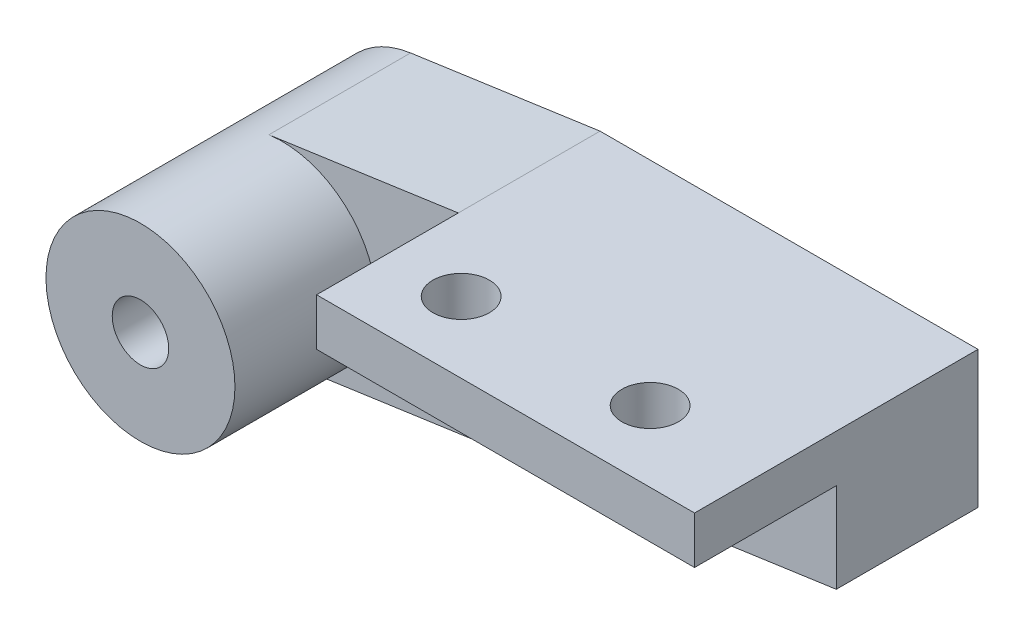
SolidWorks part; units mm, degrees
material "Custom Plastic"
ref_plane "Front Plane" through (0, 0, 0) normal (0, 0, 1) x (1, 0, 0)
ref_plane "Top Plane" through (0, 0, 0) normal (0, 1, 0) x (1, 0, 0)
ref_plane "Right Plane" through (0, 0, 0) normal (1, 0, 0) x (0, 0, -1)
sketch "Sketch1" plane through (0, 0, 0) normal (0, 0, 1) x (1, 0, 0)
  line L0 (0, 0) -> (11.8364, 0) construction
  line L1 (11.8364, 0) -> (11.8364, 8.1026) construction
  line L2 (11.8364, 8.1026) -> (-0.8967, 6.2864)
  line L3 (0.8967, -6.2864) -> (37.2364, -1.1029)
  line L4 (11.8364, 8.1026) -> (37.2364, 8.1026)
  line L5 (37.2364, 8.1026) -> (37.2364, -1.1029)
  arc A0 (-0.8967, 6.2864) -> (0.8967, -6.2864) centre (0, 0) ccw
  dimension "D3" = 12.7
  dimension "D1" = 11.8364
  dimension "D2" = 8.1026
  dimension "D4" = 25.4
extrude "Boss-Extrude1" add sketch "Sketch1" along normal blind 9.525
sketch "Sketch4" plane through (0, 0, 9.525) normal (0, 0, 1) x (1, 0, 0)
  line L0 (37.2364, -1.1029) -> (37.2364, 8.1026) construction
  line L1 (37.2364, 8.1026) -> (11.8364, 8.1026)
  line L2 (37.2364, 8.1026) -> (37.2364, 4.9276)
  line L3 (37.2364, 4.9276) -> (11.8364, 4.9276)
  line L4 (11.8364, 8.1026) -> (11.8364, 4.9276)
  line L5 (37.2364, 8.1026) -> (11.8364, 8.1026) construction
  circle A0 centre (0, 0) radius 6.35
  arc A1 (-0.8967, 6.2864) -> (0.8967, -6.2864) centre (0, 0) ccw construction
  dimension "D1" = 3.175
extrude "Boss-Extrude2" add sketch "Sketch4" along normal blind 9.525
hole_wizard "#6 Clearance Hole1" positions "3DSketch2" profile "Sketch3" hole size "#6" standard "ANSI Inch" end condition through all
sketch3d "3DSketch2"
  point P11 (0, 0, 0)
sketch "Sketch3" plane through (0, 0, 0) normal (1, 0, 0) x (0, 1, 0)
  line L0 (0, 0) -> (0, 19.05)
  line L1 (0, 19.05) -> (1.8986, 19.05)
  line L2 (1.8986, 19.05) -> (1.8986, 0)
  line L5 (1.8986, 0) -> (0, 0)
  line L11 (0, -6.35) -> (0, 107.95) construction
  dimension "Thru Hole Dia." = 3.7973
  dimension "Thru Hole Depth" = 19.05
hole_wizard "#6 Clearance Hole2" positions "3DSketch3" profile "Sketch5" hole size "#6" standard "ANSI Inch" end condition through all
sketch3d "3DSketch3"
  line L0 (16.7894, 4.9276, 14.2875) -> (29.4894, 4.9276, 14.2875) construction
  line L2 (11.8364, 4.9276, 19.05) -> (37.2364, 4.9276, 19.05) construction
  line L3 (11.8364, 4.9276, 9.525) -> (37.2364, 4.9276, 9.525) construction
  line L4 (23.1394, 4.9276, 14.2875) -> (23.1394, 4.9276, 17.5854) construction
  line L5 (37.2364, 4.9276, 19.05) -> (37.2364, 4.9276, 9.525) construction
  point P0 (16.7894, 4.9276, 14.2875)
  point P2 (29.4894, 4.9276, 14.2875)
  dimension "D1" = 9.525
  dimension "D2" = 12.7
  dimension "D3" = 28.194
sketch "Sketch5" plane through (16.7894, 4.9276, 14.2875) normal (1, 0, 0) x (0, 0, -1)
  line L0 (0, 0) -> (0, 3.175)
  line L1 (0, 3.175) -> (1.8986, 3.175)
  line L2 (1.8986, 3.175) -> (1.8986, 0)
  line L5 (1.8986, 0) -> (0, 0)
  line L11 (0, -6.35) -> (0, 107.95) construction
  dimension "Thru Hole Dia." = 3.7973
  dimension "Thru Hole Depth" = 3.175
sketch "Sketch6" [suppressed] plane through (0, 0, 0) normal (0, 0, -1) x (-1, 0, 0)
  line L0 (-46.2788, -2.5353) -> (-46.2788, 8.1026) construction
  line L1 (-20.8788, 8.1026) -> (-46.2788, 8.1026)
  line L2 (-20.8788, 8.1026) -> (-20.8788, 4.9276)
  line L3 (-20.8788, 4.9276) -> (-46.2788, 4.9276)
  line L4 (-46.2788, 8.1026) -> (-46.2788, 4.9276)
  circle A0 centre (0, 0) radius 6.35
  dimension "D1" = 3.175
extrude "Boss-Extrude3" [suppressed] add sketch "Sketch6" along normal blind 9.525
hole_wizard "#6 Clearance Hole3" [suppressed] positions "3DSketch4" profile "Sketch7" hole size "#6" standard "ANSI Inch"
sketch3d "3DSketch4"
  point P0 (0, 0, 9.525)
sketch "Sketch7" plane through (0, 0, 9.525) normal (1, 0, 0) x (0, -1, 0)
  line L0 (0, 0) -> (0, 19.05)
  line L1 (0, 19.05) -> (1.8986, 19.05)
  line L2 (1.8986, 19.05) -> (1.8986, 0)
  line L5 (1.8986, 0) -> (0, 0)
  line L11 (0, -6.35) -> (0, 107.95) construction
  dimension "Thru Hole Dia." = 3.7973
  dimension "Thru Hole Depth" = 19.05
hole_wizard "#6 Clearance Hole4" [suppressed] positions "3DSketch5" profile "Sketch8" hole size "#6" standard "ANSI Inch"
sketch3d "3DSketch5"
  line L0 (39.9288, 4.9276, -4.7625) -> (27.2288, 4.9276, -4.7625) construction
  line L2 (46.2788, 4.9276, -9.525) -> (20.8788, 4.9276, -9.525) construction
  line L3 (33.5788, 4.9276, -4.7625) -> (33.5788, 4.9276, -7.4979) construction
  line L5 (46.2788, 4.9276, -9.525) -> (46.2788, 4.9276, 0) construction
  point P0 (39.9288, 4.9276, -4.7625)
  point P2 (27.2288, 4.9276, -4.7625)
  dimension "D1" = 9.525
  dimension "D2" = 12.7
  dimension "D3" = 25.4
sketch "Sketch8" plane through (39.9288, 4.9276, -4.7625) normal (1, 0, 0) x (0, 0, -1)
  line L0 (0, 0) -> (0, 3.175)
  line L1 (0, 3.175) -> (1.8986, 3.175)
  line L2 (1.8986, 3.175) -> (1.8986, 0)
  line L5 (1.8986, 0) -> (0, 0)
  line L11 (0, -6.35) -> (0, 107.95) construction
  dimension "Thru Hole Dia." = 3.7973
  dimension "Thru Hole Depth" = 3.175
